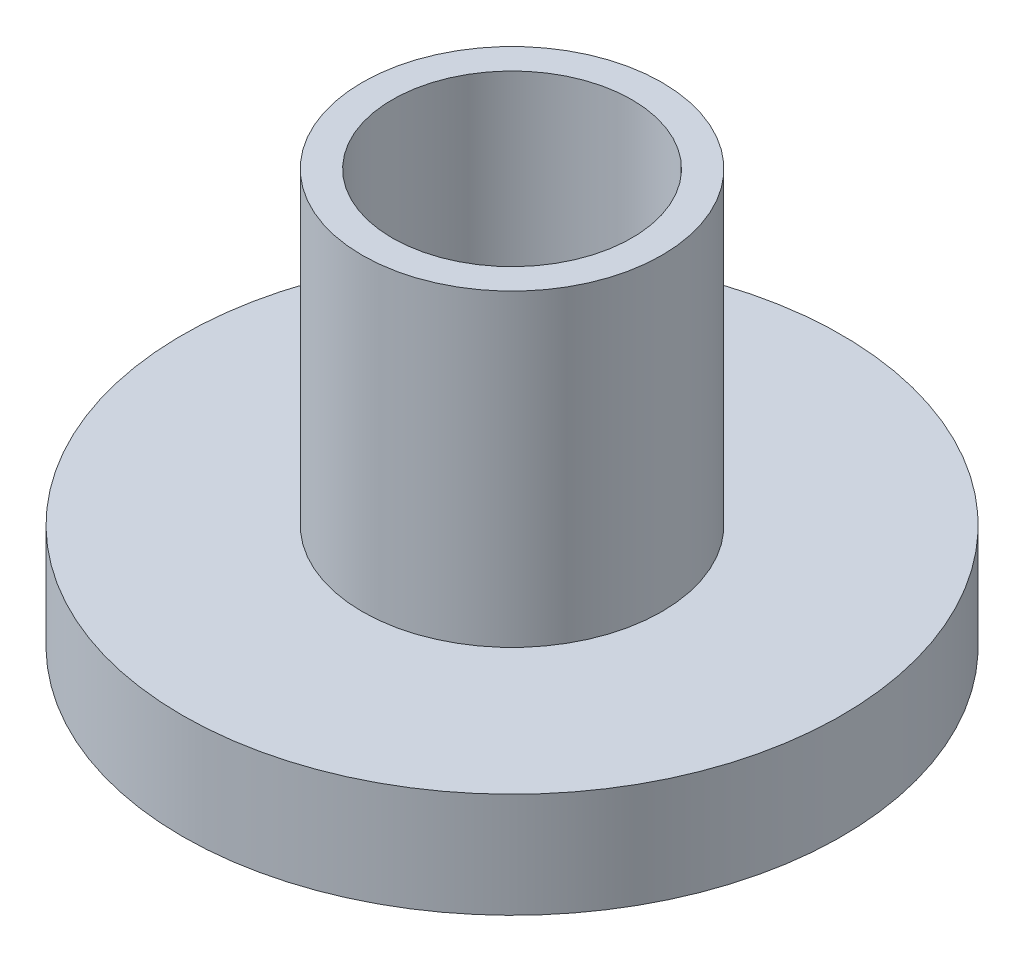
SolidWorks part; units mm, degrees
ref_plane "前视基准面" through (0, 0, 0) normal (0, 0, 1) x (1, 0, 0)
ref_plane "上视基准面" through (0, 0, 0) normal (0, 1, 0) x (1, 0, 0)
ref_plane "右视基准面" through (0, 0, 0) normal (1, 0, 0) x (0, 0, -1)
sketch "草图1" plane through (0, 0, 0) normal (0, 1, 0) x (1, 0, 0)
  circle A0 centre (0, 0) radius 5
extrude "凸台-拉伸1" add sketch "草图1" along normal blind 1.2
sketch "草图2" plane through (0, 1.2, 0) normal (0, 1, 0) x (1, 0, 0)
  circle A0 centre (0, 0) radius 11
extrude "凸台-拉伸2" add sketch "草图2" along normal blind 3.5
sketch "草图3" plane through (0, 4.7, 0) normal (0, 1, 0) x (1, 0, 0)
  circle A0 centre (0, 0) radius 5
extrude "凸台-拉伸3" add sketch "草图3" along normal blind 10.3
sketch "草图4" plane through (0, 15, 0) normal (0, 1, 0) x (1, 0, 0)
  circle A0 centre (0, 0) radius 4
extrude "切除-拉伸1" cut sketch "草图4" against normal through all
